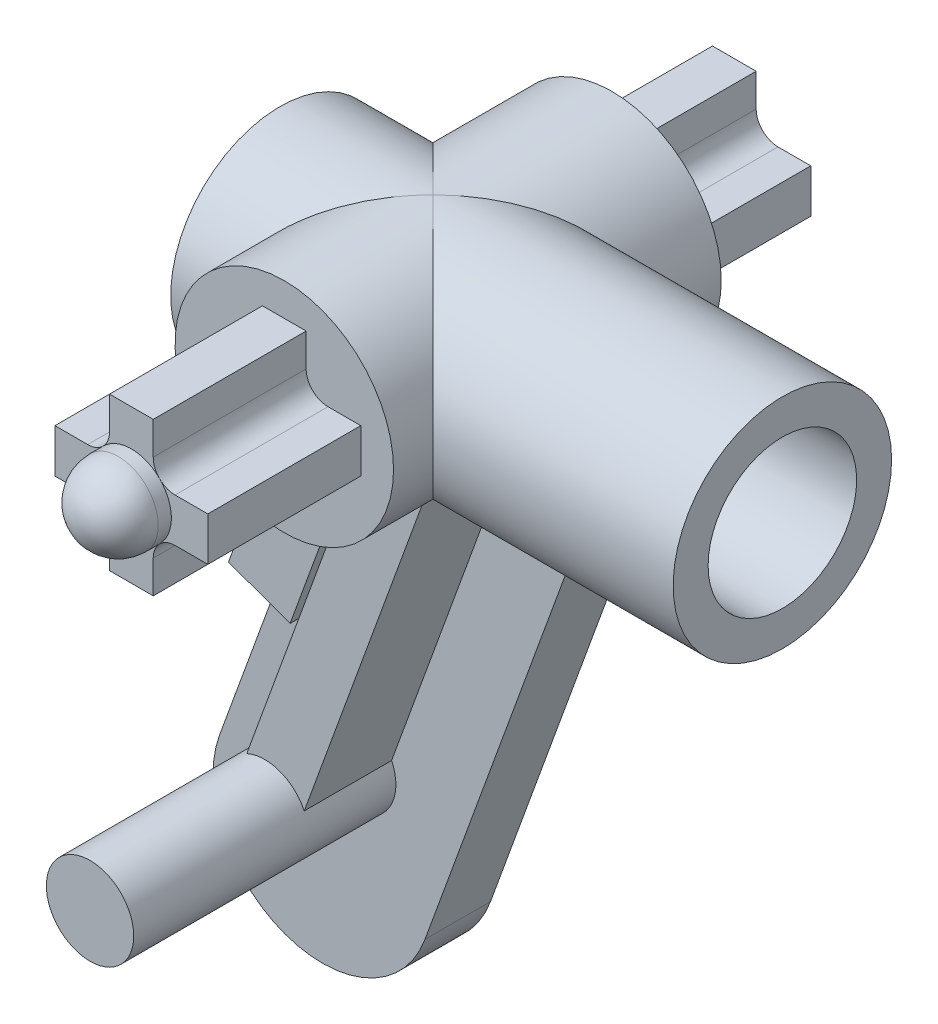
SolidWorks part; units mm, degrees
material "Nichel"
ref_plane "Piano frontale" through (0, 0, 0) normal (0, 0, 1) x (1, 0, 0)
ref_plane "Piano superiore" through (0, 0, 0) normal (0, 1, 0) x (1, 0, 0)
ref_plane "Piano destro" through (0, 0, 0) normal (1, 0, 0) x (0, 0, -1)
sketch "Schizzo1" plane through (0, 0, 0) normal (0, 0, 1) x (1, 0, 0)
  line L0 (0, 0) -> (-5.1303, -14.0954)
  line L1 (0, 0) -> (0, -9.0636) construction
  line L2 (0, 0) -> (-5.1303, -14.0954) construction
  line L3 (2.3492, -0.8551) -> (-2.7811, -14.9504)
  line L4 (-2.3492, 0.8551) -> (-7.4795, -13.2403)
  arc A1 (2.3492, -0.8551) -> (-2.3492, 0.8551) centre (0, 0) ccw
  arc A2 (-7.4795, -13.2403) -> (-2.7811, -14.9504) centre (-5.1303, -14.0954) ccw
  point P4 (-2.5652, -7.0477)
  point P11 (-5.9854, -16.4446)
  dimension "D2" = 17.5
  dimension "D3" = 2.5
  dimension "D1" = 20
extrude "Estrusione-Estrusione1" add sketch "Schizzo1" along normal blind 1.5
sketch "Schizzo2" plane through (0, 0, 0) normal (0, 0, 1) x (1, 0, 0)
  circle A0 centre (0, 0) radius 2.5
  dimension "D1" = 5
extrude "Estrusione-Estrusione2" add sketch "Schizzo2" along normal blind 7.5
sketch "Schizzo3" plane through (0, 0, 1.5) normal (0, 0, 1) x (1, 0, 0)
  line L0 (0, 0) -> (-5.1303, -14.0954) construction
  circle A0 centre (-4.4463, -12.216) radius 1
  arc A1 (-7.4795, -13.2403) -> (-2.7811, -14.9504) centre (-5.1303, -14.0954) ccw construction
  point P8 (-5.9854, -16.4446)
  dimension "D1" = 2
  dimension "D2" = 4.5
extrude "Estrusione-Estrusione3" add sketch "Schizzo3" along normal blind 6
sketch "Schizzo4" plane through (0, 0, 0) normal (1, 0, 0) x (0, 0, -1)
  line L2 (-4.1, 0) -> (-7.5, 0) construction
  line L3 (-7.5, 2.5) -> (-7.5, -2.5) construction
  circle A0 centre (-4.1, 0) radius 2.5
  dimension "D1" = 3.4
  dimension "D2" = 5
extrude "Estrusione-Estrusione8" add sketch "Schizzo4" along normal blind 8 contours A0
sketch "Schizzo5" plane through (0, 0, 0) normal (1, 0, 0) x (0, 0, -1)
  circle A0 centre (-4.1, 0) radius 2.5 construction
  circle A1 centre (-4.1, 0) radius 2.5
extrude "Estrusione-Estrusione16" add sketch "Schizzo5" against normal blind 3.5
sketch "Schizzo7" plane through (0, 0, 7.5) normal (0, 0, 1) x (1, 0, 0)
  line L0 (0, -1.75) -> (0, 1.75)
  line L2 (1.75, 0) -> (-1.75, 0)
  point P4 (0, 0)
  point P8 (0, 0)
  dimension "D1" = 3.5
  dimension "D2" = 3.5
extrude "Estrusione-Sottile1" add sketch "Schizzo7" along normal blind 3.5 thin thin type two direction wall 0.5 second wall 0.5
ref_plane "Piano3" through (0, 0, 4.1) normal (0, 0, 1) x (1, 0, 0)
fillet "Raccordo1" radius 0.5 4 edges at (0.5, 0.5, 9.25) (-0.5, 0.5, 9.25) (-0.5, -0.5, 9.25) (0.5, -0.5, 9.25)
mirror "Specchia6" about plane through (0, 0, 4.1) normal (0, 0, 1) of "Raccordo1", "Estrusione-Sottile1"
sketch "Schizzo10" plane through (0, 0, 11) normal (0, 0, 1) x (1, 0, 0)
  circle A0 centre (0, 0) radius 0.9142
  dimension "D1" = 1.8284
extrude "Estrusione-Estrusione17" add sketch "Schizzo10" along normal blind 0.3
sketch "Schizzo11" plane through (0, 0, 11.3) normal (0, 0, 1) x (1, 0, 0)
  line L0 (-0.9142, 0) -> (0.9142, 0)
  arc A0 (-0.6464, 0.6464) -> (-0.6464, -0.6464) centre (0, 0) ccw construction
  circle A1 centre (0, 0) radius 0.9142 construction
  arc A2 (0.9142, 0) -> (-0.9142, 0) centre (0, 0) ccw
revolve "Rivoluzione2" add sketch "Schizzo11" angle 360 about L0
sketch "Schizzo12" plane through (0, 0, 1.5) normal (0, 0, 1) x (1, 0, 0)
  line L0 (-5.0774, -7.5175) -> (-2.3412, 0)
  line L2 (-2.3412, 0) -> (-0.9317, -0.513)
  line L3 (-0.9317, -0.513) -> (-3.6678, -8.0306)
  line L4 (-3.6678, -8.0306) -> (-5.0774, -7.5175)
  line L8 (-2.3492, 0.8551) -> (-7.4795, -13.2403) construction
  line L9 (0, 0) -> (-2.5, 0) construction
  arc A0 (0, 2.5) -> (0, -2.5) centre (0, 0) ccw construction
  dimension "D1" = 8
  dimension "D2" = 1.5
  dimension "D3" = 0.3
extrude "Estrusione-Estrusione18" add sketch "Schizzo12" along normal blind 2.2 contours L3 L4 L0 L2
sketch "Schizzo13" plane through (0, 0, 1.5) normal (0, 0, 1) x (1, 0, 0)
  line L0 (-3.7885, -12.4554) -> (0.7449, 0)
  line L1 (-3.7885, -12.4554) -> (-5.104, -11.9766)
  line L2 (-5.104, -11.9766) -> (-0.7449, 0)
  line L4 (-0.7449, 0) -> (0.7449, 0)
  line L7 (-5.4463, -12.216) -> (-3.4463, -12.216) construction
  line L8 (-1.4786, -2.0158) -> (-3.6678, -8.0306) construction
  circle A1 centre (-4.4463, -12.216) radius 1 construction
  circle A2 centre (-4.4463, -12.216) radius 1 construction
  point P8 (-4.4463, -12.216)
  point P9 (-3.6678, -8.0306)
extrude "Estrusione-Estrusione19" add sketch "Schizzo13" along normal blind 2
hole_wizard "Foro per Vite M3-1" positions "Schizzo3D1" profile "Schizzo15" hole size "M3" standard "Ansi Metric" end condition through all
sketch3d "Schizzo3D1"
  line L0 (-3.5, 0, 4.1) -> (-1.6283, 0, 4.1) construction
  point P0 (-3.5, 0, 4.1)
sketch "Schizzo15" plane through (-3.5, 0, 4.1) normal (0, 1, 0) x (0, 0, 1)
  line L0 (0, 0) -> (0, 11.5)
  line L1 (0, 11.5) -> (1.7, 11.5)
  line L2 (1.7, 11.5) -> (1.7, 0)
  line L5 (1.7, 0) -> (0, 0)
  line L11 (0, -6.35) -> (0, 107.95) construction
  dimension "Thru Hole Dia." = 3.4
  dimension "Thru Hole Depth" = 11.5
move or copy body "Corpo-Sposta/copia1" [suppressed] bodies to move or copy 116
